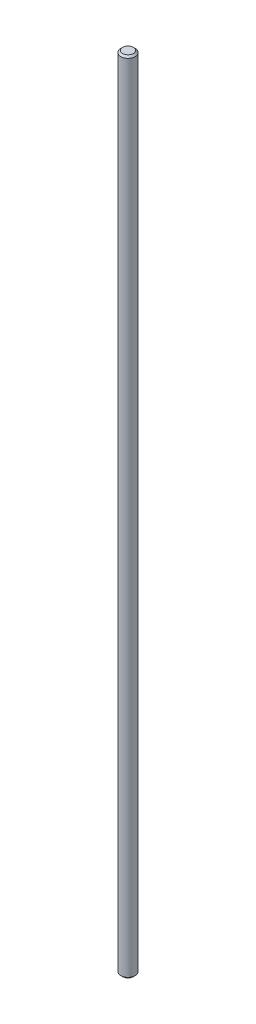
SolidWorks part; units mm, degrees
ref_plane "Front Plane" through (0, 0, 0) normal (0, 0, 1) x (1, 0, 0)
ref_plane "Top Plane" through (0, 0, 0) normal (0, 1, 0) x (1, 0, 0)
ref_plane "Right Plane" through (0, 0, 0) normal (1, 0, 0) x (0, 0, -1)
sketch "Sketch1" plane through (0, 0, 0) normal (0, 1, 0) x (1, 0, 0)
  circle A0 centre (0, 0) radius 4
extrude "Boss-Extrude1" add sketch "Sketch1" along normal blind 225 and the other way blind 220
chamfer "Chamfer1" distance 1 angle 45 2 edges at (0, 225, 4) (0, -220, 4)
